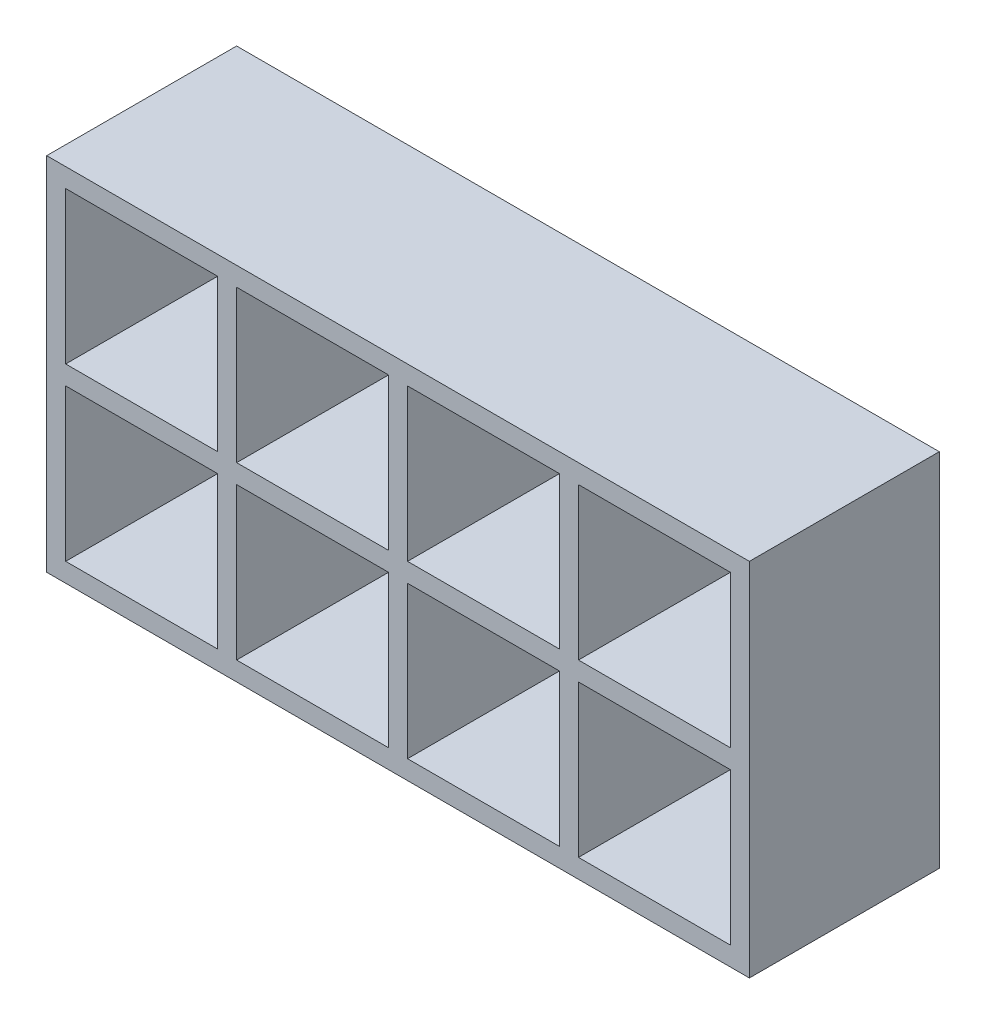
SolidWorks part; units mm, degrees
ref_plane "Front Plane" through (0, 0, 0) normal (0, 0, 1) x (1, 0, 0)
ref_plane "Top Plane" through (0, 0, 0) normal (0, 1, 0) x (1, 0, 0)
ref_plane "Right Plane" through (0, 0, 0) normal (1, 0, 0) x (0, 0, -1)
sketch "Sketch1" plane through (0, 0, 0) normal (0, 0, 1) x (1, 0, 0)
  line L0 (0, 0) -> (0, 47.5) construction
  line L1 (0, 0) -> (-185, 0)
  line L2 (0, 0) -> (0, 95)
  line L3 (0, 95) -> (-185, 95)
  line L4 (-185, 0) -> (-185, 95)
  line L5 (-180, 45) -> (-140, 45)
  line L6 (-180, 45) -> (-180, 5)
  line L7 (-180, 5) -> (-140, 5)
  line L8 (-140, 45) -> (-140, 5)
  line L9 (-135, 45) -> (-95, 45)
  line L10 (-135, 45) -> (-135, 5)
  line L11 (-135, 5) -> (-95, 5)
  line L12 (-95, 45) -> (-95, 5)
  line L13 (-90, 45) -> (-50, 45)
  line L14 (-90, 45) -> (-90, 5)
  line L15 (-90, 5) -> (-50, 5)
  line L16 (-50, 45) -> (-50, 5)
  line L17 (-45, 45) -> (-5, 45)
  line L18 (-45, 45) -> (-45, 5)
  line L19 (-45, 5) -> (-5, 5)
  line L20 (-5, 45) -> (-5, 5)
  line L21 (0, 47.5) -> (-185, 47.5) construction
  line L22 (-5, 50) -> (-5, 90)
  line L23 (-45, 90) -> (-5, 90)
  line L24 (-45, 50) -> (-45, 90)
  line L25 (-45, 50) -> (-5, 50)
  line L26 (-50, 50) -> (-50, 90)
  line L27 (-90, 90) -> (-50, 90)
  line L28 (-90, 50) -> (-90, 90)
  line L29 (-90, 50) -> (-50, 50)
  line L30 (-95, 50) -> (-95, 90)
  line L31 (-135, 90) -> (-95, 90)
  line L32 (-135, 50) -> (-135, 90)
  line L33 (-135, 50) -> (-95, 50)
  line L34 (-140, 50) -> (-140, 90)
  line L35 (-180, 90) -> (-140, 90)
  line L36 (-180, 50) -> (-180, 90)
  line L37 (-180, 50) -> (-140, 50)
  dimension "D1" = 40
  dimension "D2" = 40
  dimension "D3" = 5
  dimension "D4" = 5
  dimension "D5" = 5
  dimension "D6" = 5
  dimension "D7" = 5
  dimension "D8" = 40
  dimension "D9" = 40
  dimension "D10" = 40
  dimension "D11" = 40
  dimension "D12" = 40
  dimension "D13" = 40
  dimension "D14" = 5
  dimension "D15" = 5
  dimension "D16" = 5
  dimension "D17" = 5
  dimension "D18" = 95
  dimension "D19" = 47.5
  dimension "D20" = 185
extrude "Boss-Extrude1" add sketch "Sketch1" along normal blind 50
